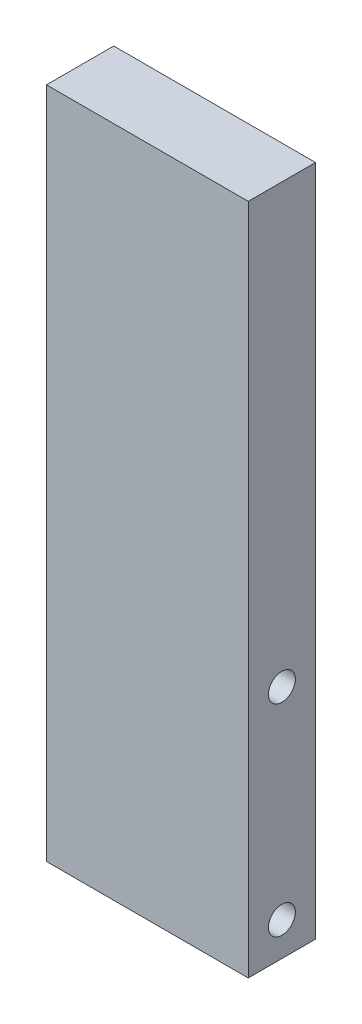
SolidWorks part; units mm, degrees
ref_plane "Front Plane" through (0, 0, 0) normal (0, 0, 1) x (1, 0, 0)
ref_plane "Top Plane" through (0, 0, 0) normal (0, 1, 0) x (1, 0, 0)
ref_plane "Right Plane" through (0, 0, 0) normal (1, 0, 0) x (0, 0, -1)
sketch "Sketch1" plane through (0, 0, 0) normal (0, 0, 1) x (1, 0, 0)
  line L1 (0, 0) -> (30, 0)
  line L2 (0, 0) -> (0, 100)
  line L3 (0, 100) -> (30, 100)
  line L4 (30, 0) -> (30, 100)
  dimension "D1" = 30
  dimension "D2" = 100
extrude "Boss-Extrude1" add sketch "Sketch1" along normal blind 10
sketch "Sketch2" plane through (30, 0, 0) normal (1, 0, 0) x (0, 0, -1)
  line L0 (-10, 0) -> (0, 0) construction
  line L1 (0, 0) -> (0, 100) construction
  circle A0 centre (-5, 5) radius 2
  circle A1 centre (-5, 35) radius 2
  dimension "D1" = 4
  dimension "D2" = 5
  dimension "D3" = 5
  dimension "D4" = 30
extrude "Cut-Extrude1" cut sketch "Sketch2" against normal through all
